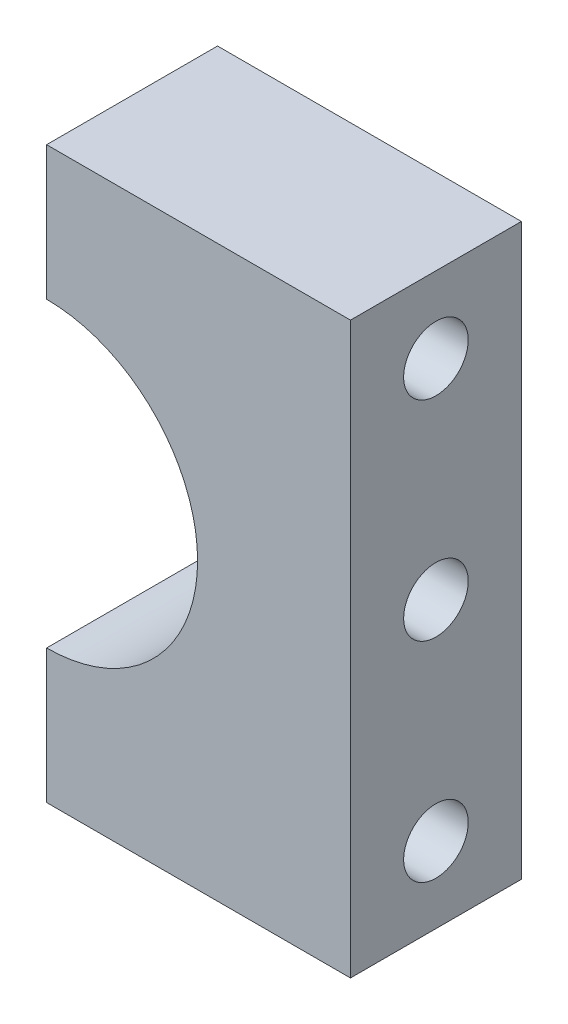
SolidWorks part; units mm, degrees
material "ABS"
ref_plane "Ön Düzlem" through (0, 0, 0) normal (0, 0, 1) x (1, 0, 0)
ref_plane "Üst Düzlem" through (0, 0, 0) normal (0, 1, 0) x (1, 0, 0)
ref_plane "Sağ Düzlem" through (0, 0, 0) normal (1, 0, 0) x (0, 0, -1)
sketch "Çizim1" plane through (0, 0, 0) normal (0, 0, 1) x (1, 0, 0)
  line L0 (16, 0) -> (16, 30) construction
  line L9 (0, 0) -> (32, 0)
  line L11 (0, 30) -> (32, 30)
  line L17 (27.5, 15) -> (4.5, 15) construction
  line L18 (0, 30) -> (0, 22)
  line L19 (0, 22) -> (0.5, 22)
  line L20 (4.5, 18) -> (4.5, 12)
  line L21 (0.5, 8) -> (0, 8)
  line L22 (0, 8) -> (0, 0)
  line L23 (32, 30) -> (32, 22)
  line L24 (32, 22) -> (31.5, 22)
  line L25 (27.5, 18) -> (27.5, 12)
  line L26 (31.5, 8) -> (32, 8)
  line L27 (32, 8) -> (32, 0)
  circle A0 centre (16, 15) radius 7.95
  arc A1 (0.5, 22) -> (4.5, 18) centre (0.5, 18) cw
  arc A2 (4.5, 12) -> (0.5, 8) centre (0.5, 12) cw
  arc A3 (31.5, 22) -> (27.5, 18) centre (31.5, 18) ccw
  arc A4 (27.5, 12) -> (31.5, 8) centre (31.5, 12) ccw
  point P21 (32, 26)
  point P22 (32, 4)
  point P27 (27.5, 22)
  dimension "D1" = 15.9
  dimension "D6" = 4
  dimension "D2" = 8
  dimension "D3" = 22
  dimension "D4" = 32
  dimension "D5" = 4.5
extrude "Yükseklik-Ekstrüzyon1" add sketch "Çizim1" along normal blind 9
sketch "Çizim2" plane through (32, 0, 0) normal (1, 0, 0) x (0, 0, -1)
  line L0 (0, 26) -> (-9, 26) construction
  line L1 (-4.5, 30) -> (-4.5, 22) construction
  line L2 (-9, 4) -> (0, 4) construction
  line L3 (-4.5, 8) -> (-4.5, 0) construction
  line L4 (0, 22) -> (0, 30)
  line L5 (0, 30) -> (-9, 30)
  line L6 (-9, 30) -> (-9, 22)
  line L7 (-9, 22) -> (0, 22)
  line L8 (0, 22) -> (0, 30) construction
  line L9 (0, 30) -> (-9, 30) construction
  line L10 (-9, 30) -> (-9, 22) construction
  line L11 (-9, 22) -> (0, 22) construction
  line L14 (0, 0) -> (0, 8)
  line L15 (0, 8) -> (-9, 8)
  line L16 (-9, 8) -> (-9, 0)
  line L17 (-9, 0) -> (0, 0)
  line L18 (0, 0) -> (0, 8) construction
  line L19 (0, 8) -> (-9, 8) construction
  line L20 (-9, 8) -> (-9, 0) construction
  line L21 (-9, 0) -> (0, 0) construction
  circle A0 centre (-4.5, 4) radius 1.7
  circle A1 centre (-4.5, 26) radius 1.7
  dimension "D3" = 3.4
  dimension "D2" = 0
  dimension "D1" = 0
extrude "Kes-Ekstrüzyon1" cut sketch "Çizim2" against normal blind 50
sketch "Çizim3" plane through (4.5, 0, 0) normal (-1, 0, 0) x (0, 0, 1)
  line L0 (0, 15) -> (9, 15) construction
  line L1 (0, 18) -> (0, 12) construction
  line L2 (9, 18) -> (9, 12) construction
  circle A0 centre (4.5, 15) radius 1.7
  dimension "D1" = 3.4
extrude "Kes-Ekstrüzyon2" cut sketch "Çizim3" against normal blind 29
sketch "Çizim4" plane through (0, 0, 0) normal (0, 0, -1) x (-1, 0, 0)
  line L0 (-16, 30) -> (-16, 0)
  line L1 (-32, 30) -> (0, 30) construction
  line L2 (0, 0) -> (-32, 0) construction
  line L6 (-16, 30) -> (11.8438, 39.5316)
  line L7 (11.8438, 39.5316) -> (11.8438, 24.557)
  line L8 (9.2411, -10.2785) -> (-16, 0)
  line L9 (9.2411, -10.2785) -> (11.8438, 24.557)
extrude "Kes-Ekstrüzyon3" cut sketch "Çizim4" against normal blind 10
sketch "Çizim5" plane through (0, 0, 0) normal (0, 0, -1) x (-1, 0, 0)
  line L0 (-32, 22) -> (-26.5919, 22)
  line L1 (-26.5919, 22) -> (-26.5919, 7.0689)
  line L2 (-26.5919, 7.0689) -> (-32, 7.0689)
  line L3 (-32, 0) -> (-32, 8) construction
  line L4 (-32, 7.0689) -> (-32, 22)
extrude "Yükseklik-Ekstrüzyon2" add sketch "Çizim5" against normal up to surface (9 mm away) up to face at (26.3578, 15, 9)
sketch "Çizim6" plane through (26.5919, 0, 0) normal (-1, 0, 0) x (0, 0, 1)
  circle A0 centre (4.5, 15) radius 1.7
  dimension "D1" = 3.4
extrude "Kes-Ekstrüzyon4" cut sketch "Çizim6" against normal blind 10
